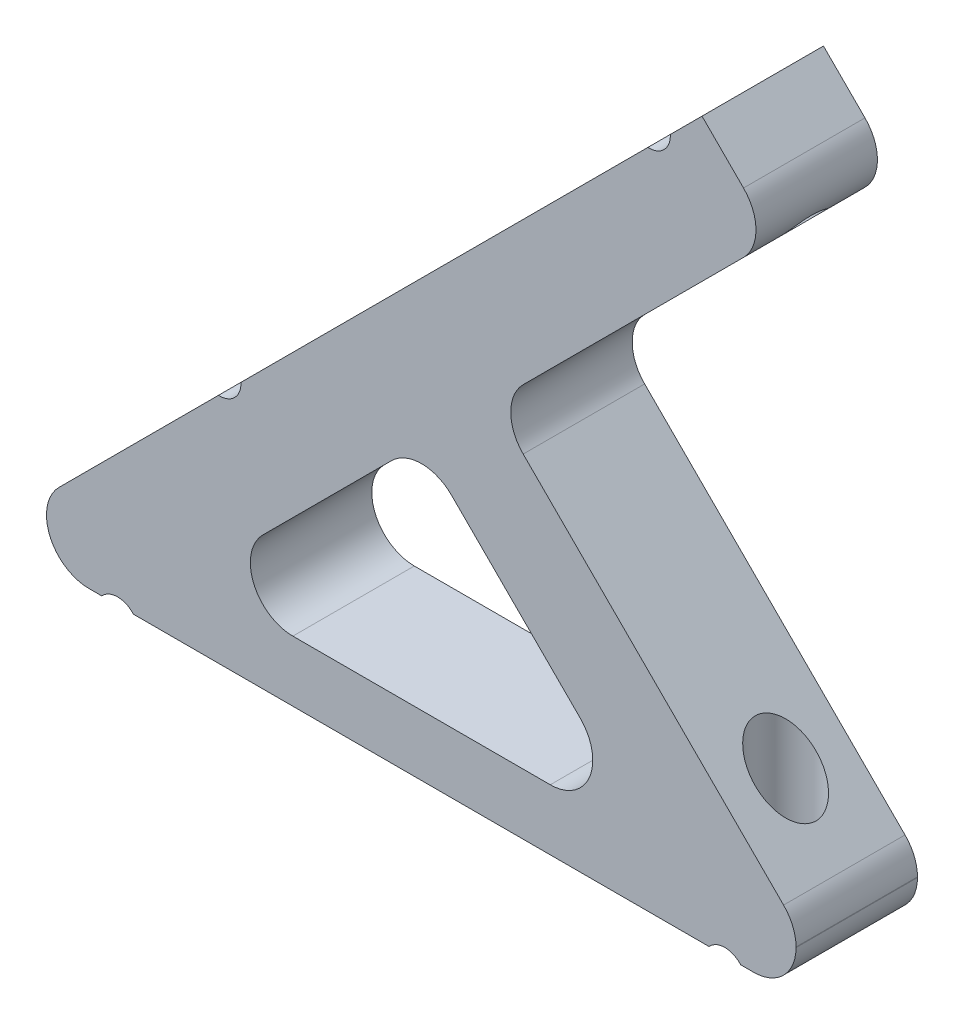
SolidWorks part; units mm, degrees
ref_plane "正面" through (0, 0, 0) normal (0, 0, 1) x (1, 0, 0)
ref_plane "平面" through (0, 0, 0) normal (0, 1, 0) x (1, 0, 0)
ref_plane "右側面" through (0, 0, 0) normal (1, 0, 0) x (0, 0, -1)
sketch "ｽｹｯﾁ1" plane through (0, 0, 0) normal (0, 0, 1) x (1, 0, 0)
  line L0 (0, 0) -> (-40, 0)
  line L1 (-40, 0) -> (-4.6447, 35.3553)
  line L2 (-4.6447, 35.3553) -> (-1.1091, 31.8198)
  line L3 (-1.1091, 31.8198) -> (-14.9645, 17.9645)
  line L4 (-14.9645, 17.9645) -> (0, 3)
  line L5 (0, 3) -> (0, 0)
  line L7 (-18.5, 14.4289) -> (-29.9289, 3)
  line L8 (-29.9289, 3) -> (-7.0711, 3)
  line L9 (-7.0711, 3) -> (-18.5, 14.4289)
  point P4 (0, 0)
  point P11 (-9.9795, 3)
  dimension "D1" = 45
  dimension "D2" = 5
  dimension "D3" = 40
  dimension "D4" = 3
  dimension "D5" = 50
  dimension "D6" = 3
  dimension "D7" = 5
extrude "ﾎﾞｽ - 押し出し1" add sketch "ｽｹｯﾁ1" along normal blind 6
fillet "ﾌｨﾚｯﾄ1" radius 2.1 8 edges at (-18.5, 14.4289, 3) (-7.0711, 3, 3) (-29.9289, 3, 3) (-1.1091, 31.8198, 3) (0, 0, 3) (0, 3, 3) (-14.9645, 17.9645, 3) (-40, 0, 3)
sketch "ｽｹｯﾁ2" plane through (0, 0, 6) normal (0, 0, 1) x (1, 0, 0)
  line L0 (-18.5151, 0) -> (-18.5151, 21.4849) construction
  line L1 (-34.9302, 0) -> (-2.1, 0) construction
  line L2 (-4.6447, 35.3553) -> (-36.4151, 3.5849) construction
  line L3 (-7.261, 33.729) -> (-28.4742, 12.5158) construction
  line L4 (-2.5941, 33.3047) -> (-4.6447, 35.3553) construction
  circle A0 centre (-33.5151, -0.7) radius 1.05
  circle A1 centre (-3.5151, -0.7) radius 1.05
  circle A2 centre (-7.261, 33.729) radius 1.05
  circle A3 centre (-28.4742, 12.5158) radius 1.05
  dimension "D1" = 2.1
  dimension "D4" = 0.7
  dimension "D2" = 0.7
  dimension "D3" = 30
  dimension "D5" = 3
  dimension "D6" = 30
extrude "ｶｯﾄ - 押し出し1" cut sketch "ｽｹｯﾁ2" against normal through all
sketch "ｽｹｯﾁ3" plane through (-20, 20, 0) normal (-0.7071, 0.7071, 0) x (0, 0, 1)
  line L0 (3, 21.7157) -> (3, -25.3144) construction
  line L1 (6, 21.7157) -> (0, 21.7157) construction
  line L2 (0, -25.3144) -> (6, -25.3144) construction
  line L3 (0, 18.7157) -> (6, 18.7157) construction
  line L4 (0, 19.4984) -> (0, 17.9331) construction
  line L5 (6, 17.9331) -> (6, 19.4984) construction
  line L6 (0, -11.2843) -> (6, -11.2843) construction
  line L7 (0, -10.5016) -> (0, -12.0669) construction
  line L8 (6, -12.0669) -> (6, -10.5016) construction
  circle A0 centre (3, 18.7157) radius 1.5
  circle A1 centre (3, -11.2843) radius 1.5
  point P22 (3, -11.2843)
  point P23 (3, 18.7157)
  point P24 (3, 17.6808)
  point P25 (3, -12.6741)
  dimension "D1" = 3
extrude "ｶｯﾄ - 押し出し2" cut sketch "ｽｹｯﾁ3" against normal up to next
sketch "ｽｹｯﾁ4" plane through (0, 0, 0) normal (0, -1, 0) x (1, 0, 0)
  line L0 (-37.0302, 3) -> (0, 3) construction
  line L1 (-37.0302, 6) -> (-37.0302, 0) construction
  line L2 (0, 6) -> (0, 0) construction
  line L3 (-33.5151, 6) -> (-33.5151, 0) construction
  line L4 (-32.7325, 6) -> (-34.2977, 6) construction
  line L5 (-34.2977, 0) -> (-32.7325, 0) construction
  line L6 (-3.5151, 6) -> (-3.5151, 0) construction
  line L7 (-2.7325, 6) -> (-4.2977, 6) construction
  line L8 (-4.2977, 0) -> (-2.7325, 0) construction
  circle A0 centre (-33.5151, 3) radius 1.5
  circle A1 centre (-3.5151, 3) radius 1.5
  dimension "D1" = 3
extrude "ｶｯﾄ - 押し出し3" cut sketch "ｽｹｯﾁ4" against normal up to next
